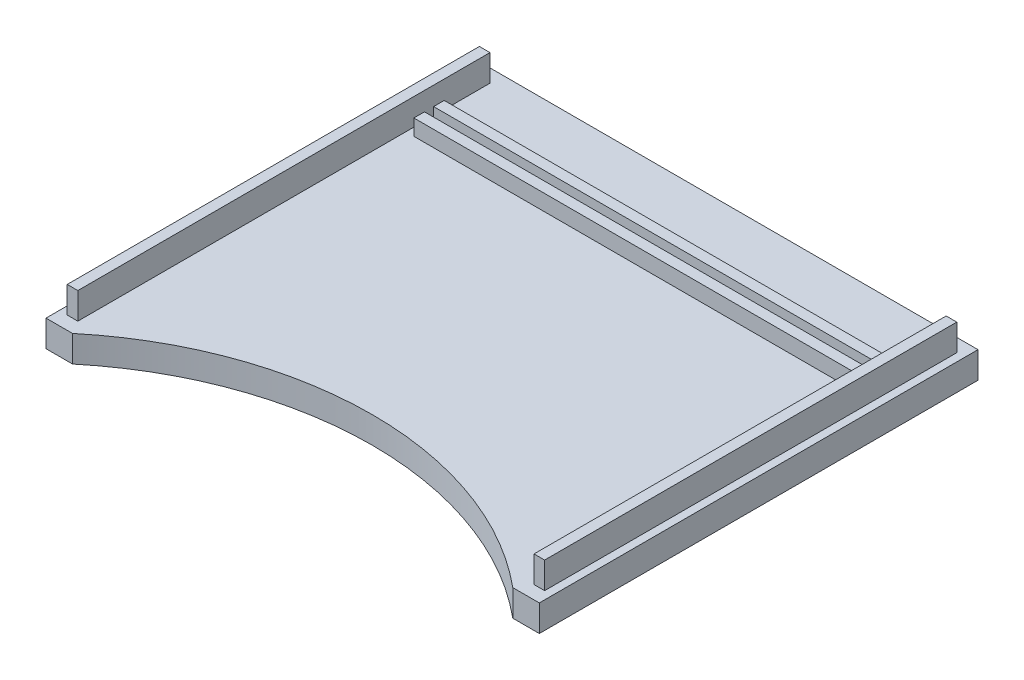
SolidWorks part; units mm, degrees
ref_plane "Front Plane" through (0, 0, 0) normal (0, 0, 1) x (1, 0, 0)
ref_plane "Top Plane" through (0, 0, 0) normal (0, 1, 0) x (1, 0, 0)
ref_plane "Right Plane" through (0, 0, 0) normal (1, 0, 0) x (0, 0, -1)
sketch "Sketch1" plane through (0, 0, 0) normal (0, 1, 0) x (1, 0, 0)
  line L1 (0, 0) -> (186, 0)
  line L2 (0, 0) -> (0, 165.4)
  line L3 (0, 165.4) -> (186, 165.4)
  line L4 (186, 0) -> (186, 165.4)
  dimension "D1" = 165.4
  dimension "D2" = 186
extrude "Boss-Extrude1" add sketch "Sketch1" along normal blind 10
sketch "Sketch4" plane through (0, 10, 0) normal (0, 1, 0) x (1, 0, 0)
  line L0 (186, 0) -> (186, 165.4) construction
  line L1 (186, 165.4) -> (0, 165.4) construction
  line L2 (10, 132.7) -> (176, 132.7)
  line L3 (10, 132.7) -> (10, 128.7)
  line L4 (10, 128.7) -> (176, 128.7)
  line L6 (10, 140.14) -> (176, 140.14)
  line L7 (176, 132.7) -> (176, 128.7)
  line L8 (0, 165.4) -> (0, 0) construction
  line L9 (10, 140.14) -> (10, 136.14)
  line L10 (10, 136.14) -> (176, 136.14)
  line L11 (176, 140.14) -> (176, 136.14)
  dimension "D1" = 4
  dimension "D2" = 32.7
  dimension "D3" = 10
  dimension "D4" = 10
  dimension "D5" = 3.44
  dimension "D6" = 4
  dimension "D7" = 10
  dimension "D8" = 10
sketch "Sketch5" plane through (0, 10, 0) normal (0, 1, 0) x (1, 0, 0)
  line L0 (10, 0) -> (10, 37.3827) construction
  line L1 (0, 0) -> (186, 0) construction
  line L2 (176, 0) -> (176, 15.4365) construction
  line L3 (0, 165.4) -> (0, 0) construction
  line L4 (186, 0) -> (186, 165.4) construction
  line L5 (93, 30) -> (0, 30) construction
  line L6 (176, 0) -> (10, 0)
  arc A0 (10, 0) -> (176, 0) centre (93, -99.8167) cw
  dimension "D1" = 10
  dimension "D2" = 10
  dimension "D3" = 30
extrude "Cut-Extrude5" cut sketch "Sketch5" against normal through all
extrude "Boss-Extrude3" add sketch "Sketch4" along normal blind 6
sketch "Sketch6" plane through (0, 10, 0) normal (0, 1, 0) x (1, 0, 0)
  line L0 (186, 165.4) -> (0, 165.4) construction
  line L1 (179, 160.4) -> (183, 160.4)
  line L2 (179, 160.4) -> (179, 5)
  line L3 (179, 5) -> (183, 5)
  line L4 (183, 160.4) -> (183, 5)
  line L5 (176, 0) -> (186, 0) construction
  line L6 (186, 0) -> (186, 165.4) construction
  dimension "D1" = 5
  dimension "D2" = 5
  dimension "D3" = 3
  dimension "D4" = 4
extrude "Boss-Extrude4" add sketch "Sketch6" along normal blind 10
sketch "Sketch7" plane through (0, 10, 0) normal (0, 1, 0) x (1, 0, 0)
  line L0 (186, 165.4) -> (0, 165.4) construction
  line L1 (3, 160.4) -> (7, 160.4)
  line L2 (3, 160.4) -> (3, 5)
  line L3 (3, 5) -> (7, 5)
  line L4 (7, 160.4) -> (7, 5)
  line L5 (0, 0) -> (10, 0) construction
  line L6 (0, 165.4) -> (0, 0) construction
  line L7 (10, 132.7) -> (10, 128.7) construction
  dimension "D1" = 5
  dimension "D2" = 5
  dimension "D3" = 3
  dimension "D4" = 3
extrude "Boss-Extrude5" add sketch "Sketch7" along normal blind 10
